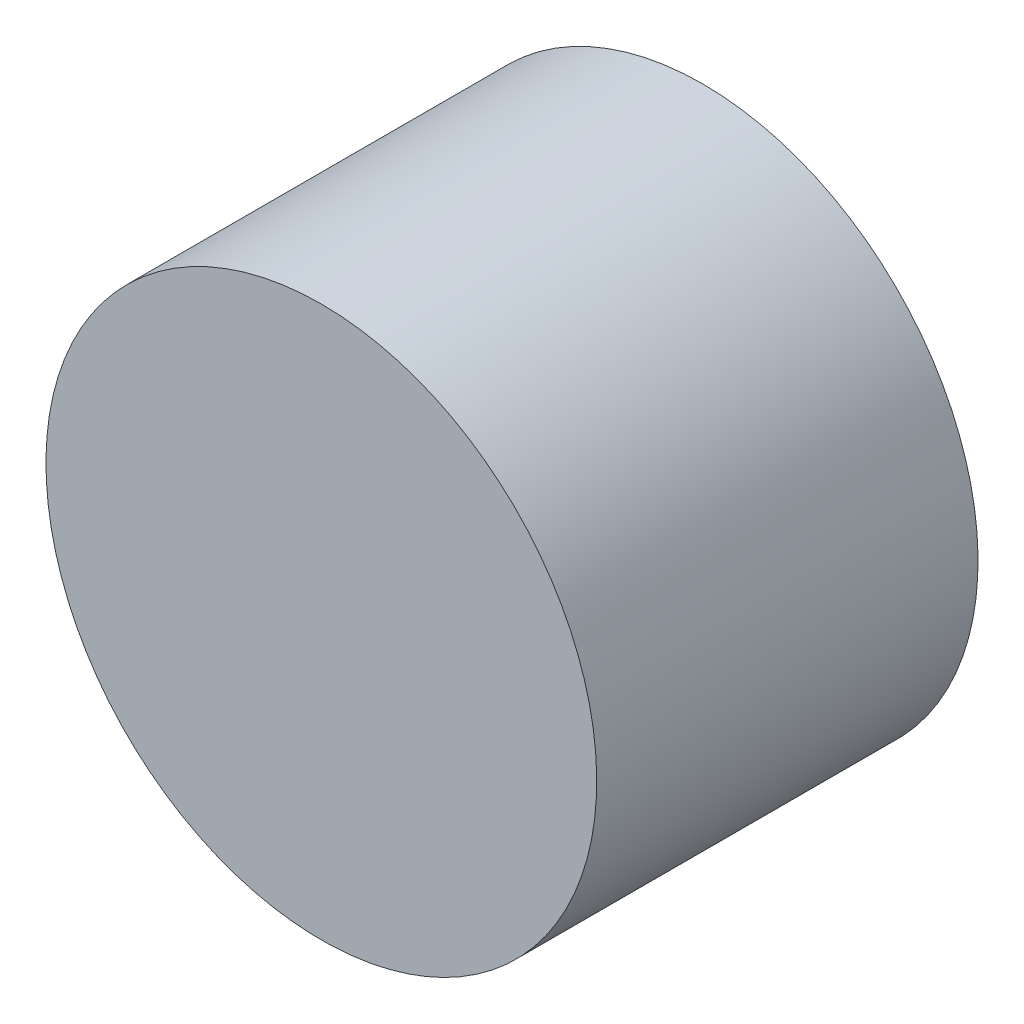
SolidWorks part; units mm, degrees
material "Alloy Steel"
ref_plane "Front Plane" through (0, 0, 0) normal (0, 0, 1) x (1, 0, 0)
ref_plane "Top Plane" through (0, 0, 0) normal (0, 1, 0) x (1, 0, 0)
ref_plane "Right Plane" through (0, 0, 0) normal (1, 0, 0) x (0, 0, -1)
sketch "Sketch1" plane through (0, 0, 0) normal (1, 0, 0) x (0, 0, -1)
  line L0 (0, 0) -> (0, 130)
  line L1 (0, 130) -> (180, 130)
  line L2 (180, 130) -> (180, 0)
  line L3 (180, 0) -> (0, 0) construction
  line L4 (0, 0) -> (180, 0)
  dimension "D1" = 260
  dimension "D2" = 180
revolve "Revolve1" add sketch "Sketch1" angle 360 about L3
